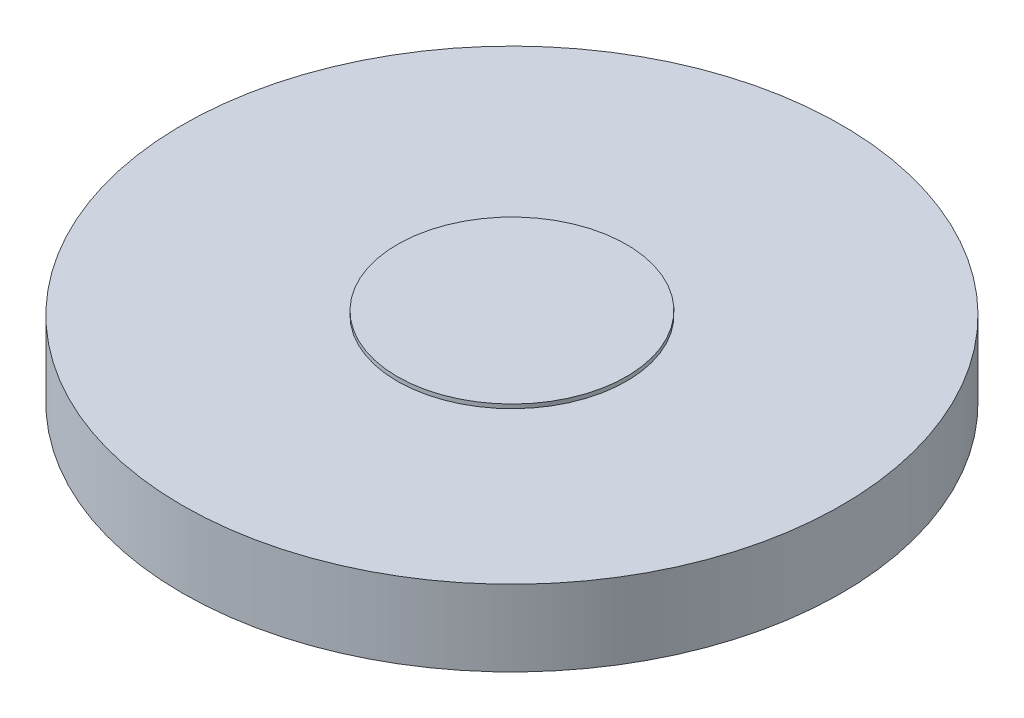
SolidWorks part; units mm, degrees
ref_plane "Front Plane" through (0, 0, 0) normal (0, 0, 1) x (1, 0, 0)
ref_plane "Top Plane" through (0, 0, 0) normal (0, 1, 0) x (1, 0, 0)
ref_plane "Right Plane" through (0, 0, 0) normal (1, 0, 0) x (0, 0, -1)
sketch "Sketch1" plane through (0, 0, 0) normal (0, 1, 0) x (1, 0, 0)
  circle A0 centre (0, 0) radius 10.414
  dimension "D1" = 20.828
extrude "Boss-Extrude1" add sketch "Sketch1" along normal blind 2.4003
sketch "Sketch2" plane through (0, 2.4003, 0) normal (0, 1, 0) x (1, 0, 0)
  circle A0 centre (0, 0) radius 4.2418
  dimension "D1" = 8.4836
extrude "Boss-Extrude2" add sketch "Sketch2" against normal blind 5.842
sketch "Sketch3" plane through (0, 2.4003, 0) normal (0, 1, 0) x (1, 0, 0)
  circle A0 centre (0, 0) radius 3.6195
  dimension "D1" = 7.239
extrude "Boss-Extrude3" add sketch "Sketch3" along normal blind 0.127
